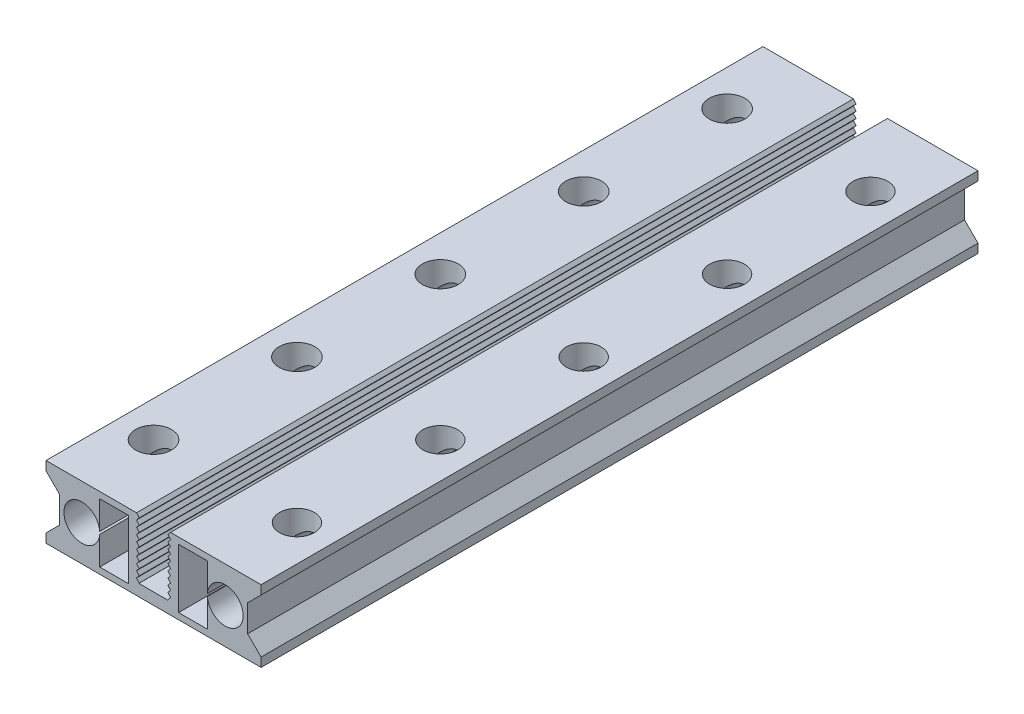
SolidWorks part; units mm, degrees
ref_plane "前视基准面" through (0, 0, 0) normal (0, 0, 1) x (1, 0, 0)
ref_plane "上视基准面" through (0, 0, 0) normal (0, 1, 0) x (1, 0, 0)
ref_plane "右视基准面" through (0, 0, 0) normal (1, 0, 0) x (0, 0, -1)
sketch "草图1" plane through (0, 0, 0) normal (0, 0, 1) x (1, 0, 0)
  line L0 (-12, 8) -> (-12, 7)
  line L1 (-12, 7) -> (-10.5, 5.5)
  line L2 (-10.5, 5.5) -> (-10.5, 2.5)
  line L3 (-10.5, 2.5) -> (-12, 1)
  line L4 (-12, 1) -> (-12, 0)
  line L5 (-12, 0) -> (12, 0)
  line L6 (12, 0) -> (12, 1)
  line L7 (12, 1) -> (10.5, 2.5)
  line L8 (10.5, 2.5) -> (10.5, 5.5)
  line L9 (10.5, 5.5) -> (12, 7)
  line L10 (12, 7) -> (12, 8)
  line L11 (12, 8) -> (1.9, 8)
  line L12 (0, 0) -> (0, 8) construction
  line L13 (-8, 4) -> (8, 4) construction
  line L14 (-1.9, 8) -> (-1.9, 1.3)
  line L15 (-6.005, 7.3) -> (-2.8, 7.3)
  line L16 (-6.005, 7.3) -> (-6.005, 4.1413)
  line L17 (-6.005, 0.7) -> (-2.8, 0.7)
  line L18 (-2.8, 7.3) -> (-2.8, 0.7)
  line L19 (-1.9, 1.3) -> (1.9, 1.3)
  line L20 (1.9, 1.3) -> (1.9, 8)
  line L21 (-1.9, 8) -> (-12, 8)
  line L22 (-6.005, 3.8587) -> (-6.005, 0.7)
  line L23 (2.8, 7.3) -> (6.005, 7.3)
  line L24 (2.8, 7.3) -> (2.8, 0.7)
  line L25 (2.8, 0.7) -> (6.005, 0.7)
  line L26 (6.005, 7.3) -> (6.005, 4.1413)
  line L27 (6.005, 3.8587) -> (6.005, 0.7)
  arc A0 (-6.005, 4.1413) -> (-6, 4) centre (-8, 4) ccw
  arc A1 (6.005, 3.8587) -> (6.005, 4.1413) centre (8, 4) ccw
  point P19 (10.5, 4)
  point P24 (-2.8, 4)
  point P27 (0, 1.3)
  dimension "D4" = 4
  dimension "D1" = 24
  dimension "D2" = 8
  dimension "D3" = 45
  dimension "D5" = 16
  dimension "D6" = 8
  dimension "D7" = 3
  dimension "D8" = 1
  dimension "D9" = 4
  dimension "D10" = 3.8
  dimension "D11" = 1.3
  dimension "D12" = 5.6
  dimension "D13" = 2.8
  dimension "D14" = 12.01
  dimension "D15" = 0.7
extrude "凸台-拉伸2" add sketch "草图1" along normal blind 80 contours L14 L21 L0 L1 L2 L3 L4 L5 L6 L7 L8 L9 L10 L11 L20 L19 A1 L27 L25 L24 L23 L26 A0 L16 L15 L18 L17 L22
sketch "草图3" plane through (0, 0, 80) normal (0, 0, 1) x (1, 0, 0)
  line L0 (-1.9, 8) -> (-1.6, 7.65)
  line L1 (-1.6, 7.65) -> (-1.9, 7.3)
  line L2 (-1.9, 8) -> (-1.9, 1.3) construction
  line L3 (-1.9, 7.3) -> (-1.9, 8)
  point P7 (-1.9, 7.65)
  dimension "D1" = 0.7
  dimension "D2" = 0.3
extrude "凸台-拉伸3" add sketch "草图3" against normal up to surface (80 mm away) up to face at (5.6025, 4, 0)
pattern_linear "阵列(线性)1" count 10 spacing 0.7 along (0, -1, 0) of "凸台-拉伸3"
mirror "镜向1" about plane through (0, 0, 0) normal (1, 0, 0) of "阵列(线性)1", "凸台-拉伸3"
sketch "草图4" plane through (0, 8, 0) normal (0, 1, 0) x (1, 0, 0)
  line L1 (12, 0) -> (1.9, 0) construction
  circle A0 centre (-8, -8) radius 2
  circle A1 centre (8, -8) radius 1.95
  dimension "D1" = 16
  dimension "D4" = 3.9
  dimension "D5" = 4
  dimension "D2" = 8
  dimension "D3" = 8
extrude "切除-拉伸1" cut sketch "草图4" against normal through all
pattern_linear "阵列(线性)2" count 5 spacing 16 along (0, 0, 1) of "切除-拉伸1"
equation "\"D13@草图1\"=\"D12@草图1\"/2"
